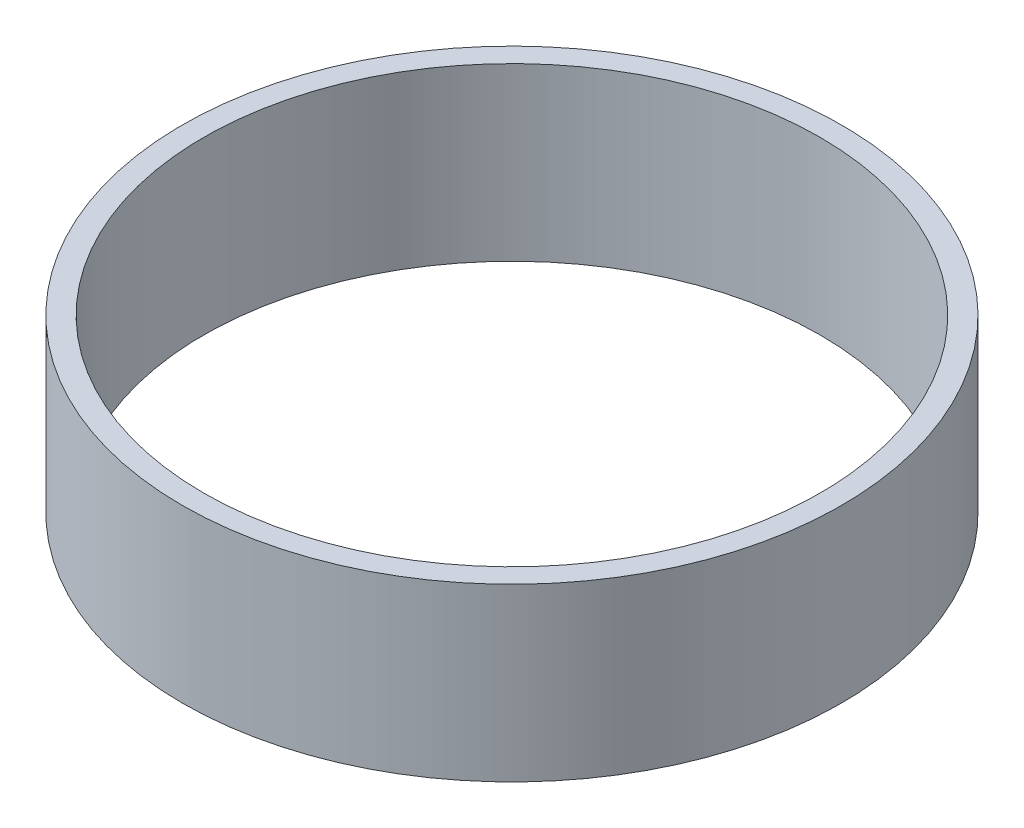
SolidWorks part; units mm, degrees
material "6061 Alloy"
ref_plane "Front Plane" through (0, 0, 0) normal (0, 0, 1) x (1, 0, 0)
ref_plane "Top Plane" through (0, 0, 0) normal (0, 1, 0) x (1, 0, 0)
ref_plane "Right Plane" through (0, 0, 0) normal (1, 0, 0) x (0, 0, -1)
sketch "Sketch1" plane through (0, 0, 0) normal (0, 1, 0) x (1, 0, 0)
  circle A0 centre (1.4149, 0.5977) radius 21.6
  circle A1 centre (1.4149, 0.5977) radius 23.1
  dimension "D1" = 1.5
extrude "Boss-Extrude1" add sketch "Sketch1" along normal blind 12
